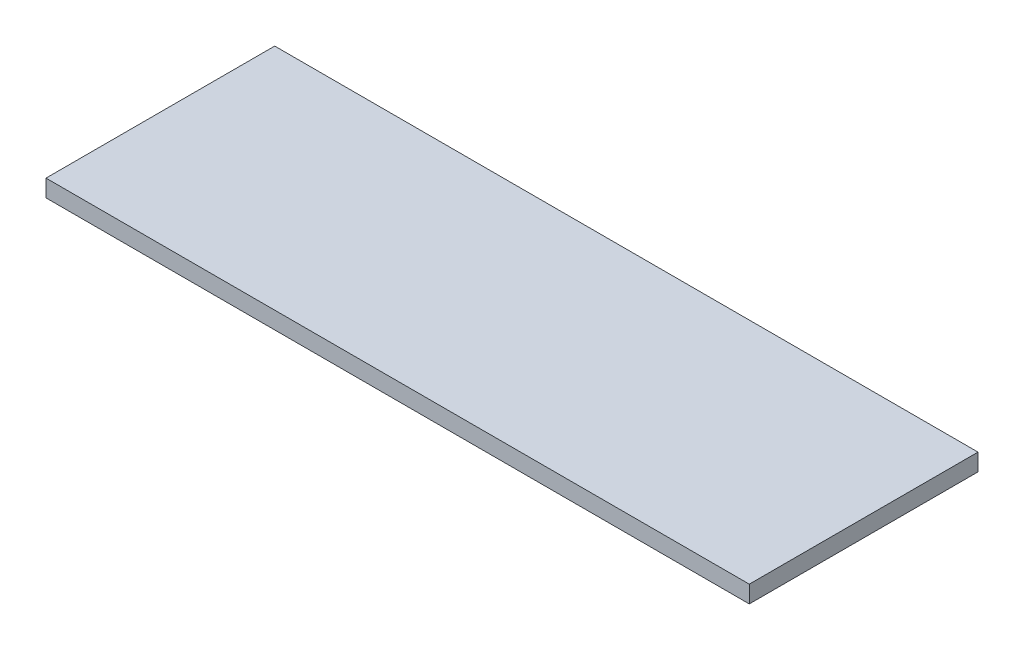
SolidWorks part; units mm, degrees
ref_plane "Alzado" through (0, 0, 0) normal (0, 0, 1) x (1, 0, 0)
ref_plane "Planta" through (0, 0, 0) normal (0, 1, 0) x (1, 0, 0)
ref_plane "Vista lateral" through (0, 0, 0) normal (1, 0, 0) x (0, 0, -1)
sketch "Croquis1" plane through (0, 0, 0) normal (0, 1, 0) x (1, 0, 0)
  line L1 (-307.5, -100) -> (307.5, -100)
  line L2 (-307.5, -100) -> (-307.5, 100)
  line L3 (-307.5, 100) -> (307.5, 100)
  line L4 (307.5, -100) -> (307.5, 100)
  line L5 (-307.5, -100) -> (307.5, 100) construction
  line L6 (-307.5, 100) -> (307.5, -100) construction
  point P0 (0, 0)
  dimension "D1" = 200
  dimension "D2" = 615
extrude "Saliente-Extruir1" add sketch "Croquis1" along normal blind 15
